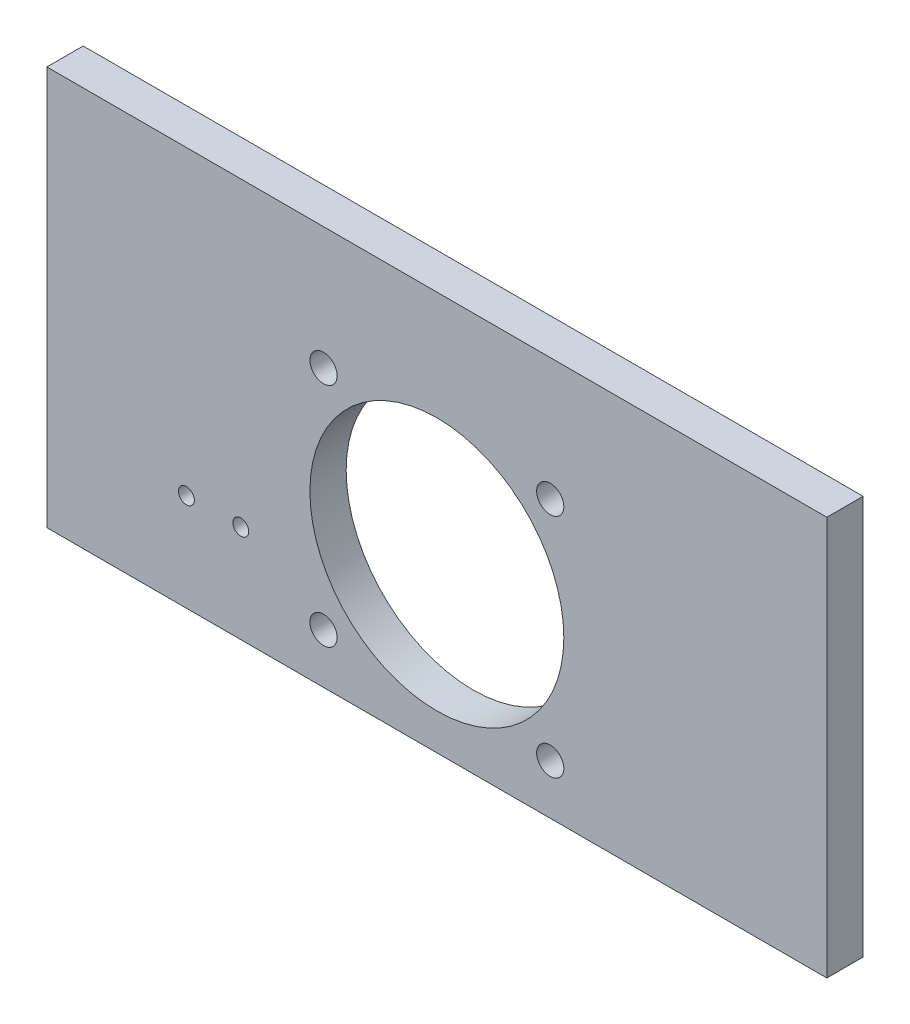
SolidWorks part; units mm, degrees
ref_plane "Płaszczyzna przednia" through (0, 0, 0) normal (0, 0, 1) x (1, 0, 0)
ref_plane "Płaszczyzna górna" through (0, 0, 0) normal (0, 1, 0) x (1, 0, 0)
ref_plane "Płaszczyzna prawa" through (0, 0, 0) normal (1, 0, 0) x (0, 0, -1)
sketch "Sketch1" plane through (0, 0, 0) normal (0, 0, 1) x (1, 0, 0)
  line L1 (0, 0) -> (86, 0)
  line L2 (0, 0) -> (0, 44)
  line L3 (0, 44) -> (86, 44)
  line L4 (86, 0) -> (86, 44)
  line L5 (0, 0) -> (86, 44) construction
  line L6 (0, 44) -> (86, 0) construction
  point P4 (43, 22)
  dimension "D1" = 86
  dimension "D2" = 44
extrude "Boss-Extrude1" add sketch "Sketch1" along normal blind 4
sketch "Sketch2" plane through (0, 0, 4) normal (0, 0, 1) x (1, 0, 0)
  line L0 (86, 44) -> (0, 44) construction
  line L1 (86, 0) -> (86, 44) construction
  circle A0 centre (43, 18) radius 14
  dimension "D1" = 28
  dimension "D2" = 26
  dimension "D3" = 43
extrude "Cut-Extrude1" cut sketch "Sketch2" against normal blind 4
sketch "Sketch3" plane through (0, 0, 4) normal (0, 0, 1) x (1, 0, 0)
  line L1 (28, 33) -> (58, 33) construction
  line L2 (28, 33) -> (28, 3) construction
  line L3 (28, 3) -> (58, 3) construction
  line L4 (58, 33) -> (58, 3) construction
  line L5 (28, 33) -> (58, 3) construction
  line L6 (28, 3) -> (58, 33) construction
  circle A0 centre (43, 18) radius 14 construction
  circle A1 centre (30.5, 30.5) radius 1.5
  circle A5 centre (55.5, 30.5) radius 1.5
  circle A6 centre (55.5, 5.5) radius 1.5
  circle A7 centre (30.5, 5.5) radius 1.5
  point P4 (43, 18)
  dimension "D4" = 3
  dimension "D5" = 2.5
  dimension "D6" = 2.5
  dimension "D1" = 30
  dimension "D2" = 15
  dimension "D3" = 15
  dimension "D7" = 4
extrude "Cut-Extrude3" cut sketch "Sketch3" against normal blind 4
hole_wizard "Ø1.0mm Dowel Hole1" positions "Sketch5" profile "Sketch6" hole size "Ø1.0" standard "ANSI Metric" end condition through all
sketch "Sketch5" plane through (0, 0, 4) normal (0, 0, 1) x (1, 0, 0)
  line L0 (0, 0) -> (86, 0) construction
  line L1 (0, 44) -> (0, 0) construction
  point P0 (15.38, 10.75)
  point P2 (21.38, 10.75)
  dimension "D1" = 10.75
  dimension "D2" = 6
  dimension "D3" = 15.38
sketch "Sketch6" plane through (15.38, 10.75, 4) normal (1, 0, 0) x (0, -1, 0)
  line L0 (0, 0) -> (0, 4)
  line L1 (0, 4) -> (0.875, 4)
  line L2 (0.875, 4) -> (0.875, 0)
  line L5 (0.875, 0) -> (0, 0)
  line L11 (0, -6.35) -> (0, 107.95) construction
  dimension "Thru Hole Dia." = 1.75
  dimension "Thru Hole Depth" = 4
